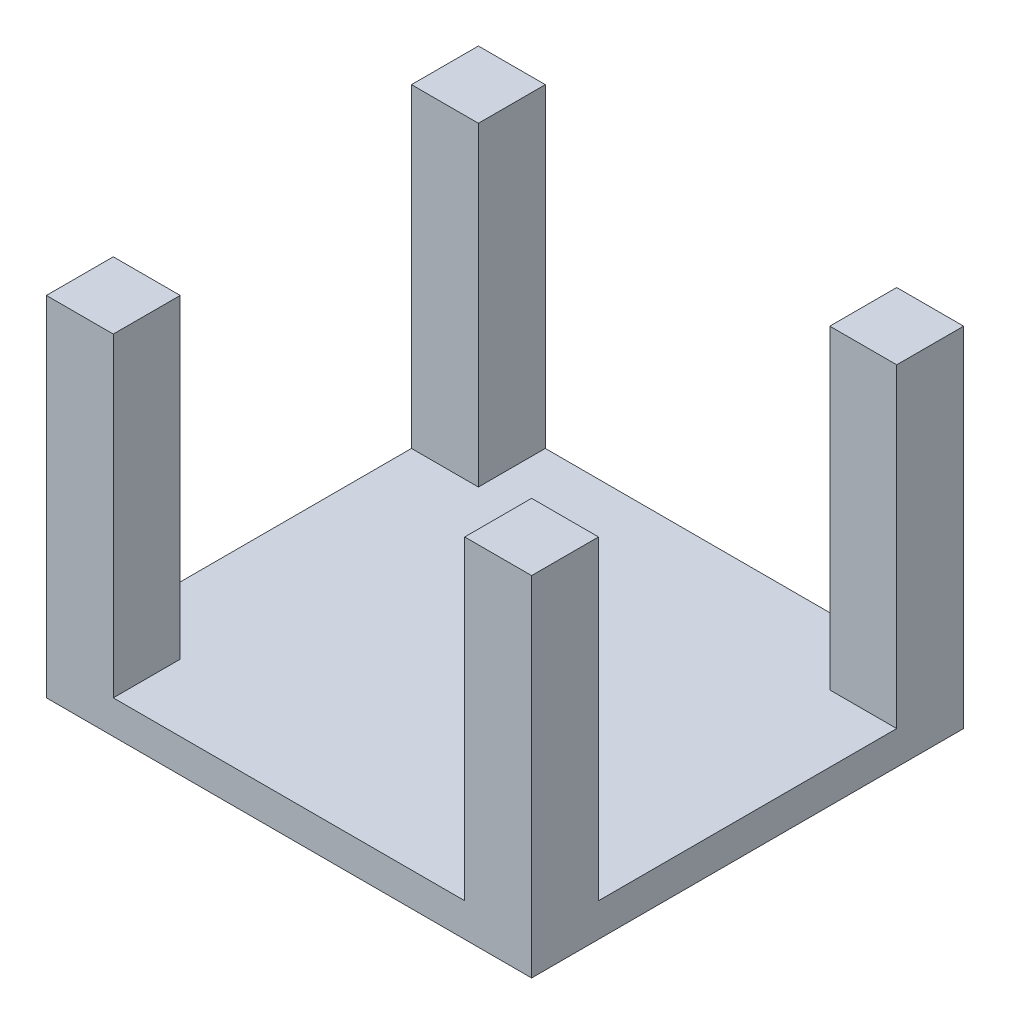
SolidWorks part; units mm, degrees
ref_plane "Front Plane" through (0, 0, 0) normal (0, 0, 1) x (1, 0, 0)
ref_plane "Top Plane" through (0, 0, 0) normal (0, 1, 0) x (1, 0, 0)
ref_plane "Right Plane" through (0, 0, 0) normal (1, 0, 0) x (0, 0, -1)
sketch "Sketch1" plane through (0, 0, 0) normal (0, 1, 0) x (1, 0, 0)
  line L1 (-46.05, -41) -> (46.05, -41)
  line L2 (-46.05, -41) -> (-46.05, 41)
  line L3 (-46.05, 41) -> (46.05, 41)
  line L4 (46.05, -41) -> (46.05, 41)
  line L5 (-46.05, -41) -> (46.05, 41) construction
  line L6 (-46.05, 41) -> (46.05, -41) construction
  point P0 (0, 0)
  dimension "D1" = 82
  dimension "D2" = 92.1
extrude "Boss-Extrude3" add sketch "Sketch1" along normal blind 6.35
sketch "Sketch2" plane through (0, 6.35, 0) normal (0, 1, 0) x (1, 0, 0)
  line L0 (0, -3.4925) -> (0, 3.4925) construction
  line L1 (-46.05, 41) -> (-33.35, 41)
  line L2 (-46.05, 41) -> (-46.05, 28.3)
  line L3 (-46.05, 28.3) -> (-33.35, 28.3)
  line L4 (-33.35, 41) -> (-33.35, 28.3)
  line L5 (-46.05, 41) -> (-33.35, 28.3) construction
  line L6 (-46.05, 28.3) -> (-33.35, 41) construction
  line L7 (46.05, 28.3) -> (33.35, 28.3)
  line L8 (33.35, 41) -> (33.35, 28.3)
  line L9 (46.05, 41) -> (33.35, 41)
  line L10 (46.05, 41) -> (46.05, 28.3)
  line L11 (46.05, 28.3) -> (33.35, 41) construction
  line L12 (46.05, 41) -> (33.35, 28.3) construction
  line L13 (-3.4925, 0) -> (3.4925, 0) construction
  line L14 (46.05, -41) -> (46.05, -28.3)
  line L15 (46.05, -41) -> (33.35, -41)
  line L16 (33.35, -41) -> (33.35, -28.3)
  line L17 (46.05, -28.3) -> (33.35, -28.3)
  line L18 (-46.05, -28.3) -> (-33.35, -28.3)
  line L19 (-33.35, -41) -> (-33.35, -28.3)
  line L20 (-46.05, -41) -> (-33.35, -41)
  line L21 (-46.05, -41) -> (-46.05, -28.3)
  point P4 (-39.7, 34.65)
  point P12 (39.7, 34.65)
  dimension "D1" = 12.7
extrude "Boss-Extrude4" add sketch "Sketch2" along normal blind 59.8
